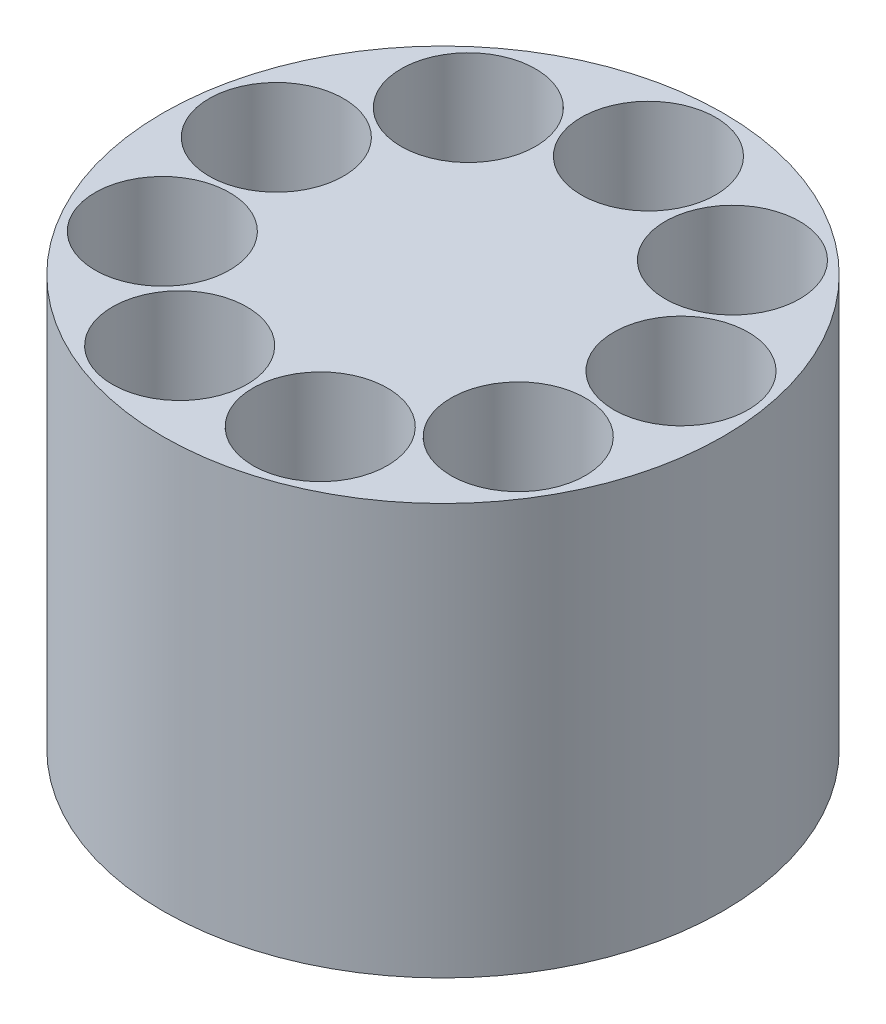
SolidWorks part; units mm, degrees
ref_plane "前基準面" through (0, 0, 0) normal (0, 0, 1) x (1, 0, 0)
ref_plane "上基準面" through (0, 0, 0) normal (0, 1, 0) x (1, 0, 0)
ref_plane "右基準面" through (0, 0, 0) normal (1, 0, 0) x (0, 0, -1)
sketch "草圖1" plane through (0, 0, 0) normal (0, 1, 0) x (1, 0, 0)
  line L0 (-19.7711, 0) -> (21.1053, 0) construction
  circle A0 centre (0, 0) radius 150
  circle A1 centre (0, 110) radius 36
  circle A2 centre (70.7066, 84.2649) radius 36
  circle A3 centre (108.3289, 19.1013) radius 36
  circle A4 centre (95.2628, -55) radius 36
  circle A5 centre (37.6222, -103.3662) radius 36
  circle A6 centre (-37.6222, -103.3662) radius 36
  circle A7 centre (-95.2628, -55) radius 36
  circle A8 centre (-108.3289, 19.1013) radius 36
  circle A9 centre (-70.7066, 84.2649) radius 36
  arc A10 (12.2474, 2.5) -> (12.2474, -2.5) centre (0, 0) ccw
  arc A11 (12.2474, 2.5) -> (12.2474, -2.5) centre (0, 0) cw
  point P23 (0, 0)
  dimension "D1" = 72
  dimension "D4" = 300
  dimension "D5" = 25
  dimension "D2" = 110
  dimension "D3" = 9
extrude "填料-伸長1" add sketch "草圖1" along normal blind 220
sketch "草圖2" plane through (0, 220, 0) normal (0, 1, 0) x (1, 0, 0)
  circle A0 centre (0, 0) radius 12.5
extrude "填料-伸長2" add sketch "草圖2" against normal blind 10
sketch "草圖4" plane through (0, 0, 0) normal (0, -1, 0) x (1, 0, 0)
  line L0 (15.1004, 8.8446) -> (48.4279, 35.4223)
  line L1 (2.5, 12.2474) -> (-2.5, 12.2474) construction
  line L2 (2.5, 17.3205) -> (2.5, 59.9479)
  line L4 (-2.5, 17.3205) -> (-2.5, 59.9479)
  line L5 (11.983, 12.7537) -> (45.3104, 39.3315)
  line L6 (16.3299, -6.2915) -> (57.8886, -15.777)
  line L7 (17.4425, -1.4169) -> (59.0012, -10.9023)
  line L8 (5.2627, -16.6899) -> (23.758, -55.0959)
  line L9 (9.7675, -14.5205) -> (28.2628, -52.9265)
  line L10 (-9.7675, -14.5205) -> (-28.2628, -52.9265)
  line L11 (-5.2627, -16.6899) -> (-23.758, -55.0959)
  line L12 (-17.4425, -1.4169) -> (-59.0012, -10.9023)
  line L13 (-16.3299, -6.2915) -> (-57.8886, -15.777)
  line L14 (-11.983, 12.7537) -> (-45.3104, 39.3315)
  line L15 (-15.1004, 8.8446) -> (-48.4279, 35.4223)
  arc A0 (-2.5, 59.9479) -> (-45.3104, 39.3315) centre (0, 0) ccw
  arc A3 (-57.8886, -15.777) -> (-28.2628, -52.9265) centre (0, 0) ccw
  arc A4 (-48.4279, 35.4223) -> (-59.0012, -10.9023) centre (0, 0) ccw
  arc A8 (45.3104, 39.3315) -> (2.5, 59.9479) centre (0, 0) ccw
  arc A9 (59.0012, -10.9023) -> (48.4279, 35.4223) centre (0, 0) ccw
  arc A10 (28.2628, -52.9265) -> (57.8886, -15.777) centre (0, 0) ccw
  arc A11 (-23.758, -55.0959) -> (23.758, -55.0959) centre (0, 0) ccw
  arc A15 (-16.3299, -6.2915) -> (-9.7675, -14.5205) centre (0, 0) ccw
  circle A16 centre (0, 0) radius 12.5 construction
  arc A17 (-15.1004, 8.8446) -> (-17.4425, -1.4169) centre (0, 0) ccw
  arc A18 (-5.2627, -16.6899) -> (5.2627, -16.6899) centre (0, 0) ccw
  arc A19 (9.7675, -14.5205) -> (16.3299, -6.2915) centre (0, 0) ccw
  arc A20 (17.4425, -1.4169) -> (15.1004, 8.8446) centre (0, 0) ccw
  arc A21 (11.983, 12.7537) -> (2.5, 17.3205) centre (0, 0) ccw
  arc A22 (-2.5, 17.3205) -> (-11.983, 12.7537) centre (0, 0) ccw
  point P10 (0, 12.2474)
  point P36 (0, 0)
  dimension "D1" = 120
  dimension "D4" = 5
  dimension "D2" = 5
  dimension "D3" = 7
